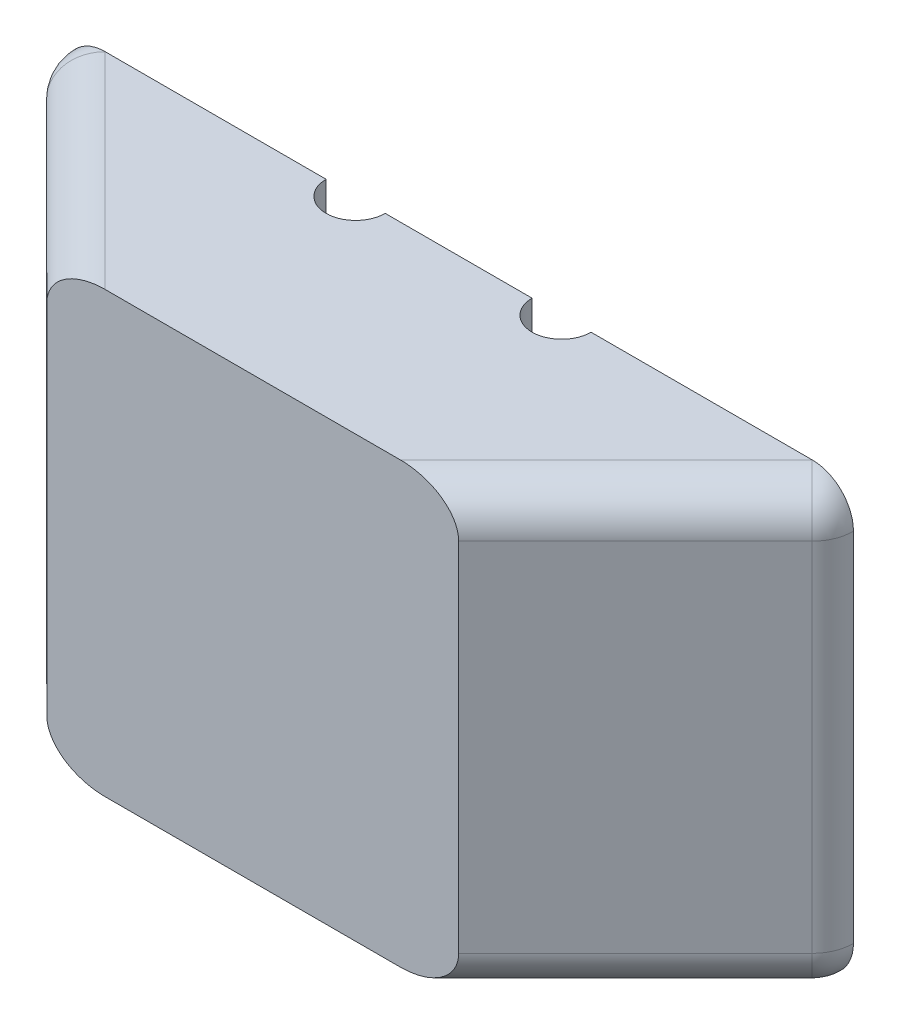
SolidWorks part; units mm, degrees
material "PLA+"
ref_plane "Front Plane" through (0, 0, 0) normal (0, 0, 1) x (1, 0, 0)
ref_plane "Top Plane" through (0, 0, 0) normal (0, 1, 0) x (1, 0, 0)
ref_plane "Right Plane" through (0, 0, 0) normal (1, 0, 0) x (0, 0, -1)
sketch "Sketch1" plane through (0, 0, 0) normal (0, 1, 0) x (1, 0, 0)
  line L0 (15, 15) -> (30, -0.0187)
  line L5 (15, 15) -> (-15, 15)
  line L6 (15, 15) -> (15, -15)
  line L7 (15, -15) -> (-15, -15)
  line L8 (-15, 15) -> (-15, -15)
  line L9 (15, 15) -> (-15, -15) construction
  line L10 (15, -15) -> (-15, 15) construction
  line L11 (30, -0.0187) -> (15, -15)
  line L12 (0, 15) -> (0, -15) construction
  line L13 (-30, -0.0187) -> (-15, -15)
  line L14 (-15, 15) -> (-30, -0.0187)
  point P0 (0, 0)
  dimension "D3" = 15
  dimension "D4" = 90
  dimension "D1" = 30
  dimension "D2" = 21.2
extrude "Boss-Extrude2" add sketch "Sketch1" along normal blind 32 contours L8 L14 L13 | L5 L8 L7 L6 | L11 L0 L6
fillet "Fillet1" radius 3 10 edges at (-22.5, 0, -7.4907) (-22.5, 32, -7.4907) (-22.5, 0, 7.5094) (-22.5, 32, 7.5094) (-30, 16, 0.0187) (30, 16, 0.0187) (22.5, 0, 7.5094) (22.5, 32, 7.5094) (22.5, 0, -7.4907) (22.5, 32, -7.4907)
sketch "Sketch3" plane through (0, 32, 0) normal (0, 1, 0) x (1, 0, 0)
  line L0 (25.7574, 0.016) -> (-25.7574, -0.016) construction
  circle A0 centre (-7.5, -0.0047) radius 2.15
  circle A1 centre (7.5, 0.0047) radius 2.15
  point P5 (0, 0)
  dimension "D2" = 4.3
  dimension "D4" = 4.3
  dimension "D1" = 7.5
  dimension "D3" = 7.5
extrude "Cut-Extrude1" cut sketch "Sketch3" against normal blind 63
sketch "Sketch5" plane through (0, 0, 0) normal (0, 0, 1) x (1, 0, 0)
  line L1 (-35.9882, 37.6239) -> (42.0689, 37.6239)
  line L2 (-35.9882, 37.6239) -> (-35.9882, -0.8462)
  line L3 (-35.9882, -0.8462) -> (42.0689, -0.8462)
  line L4 (42.0689, 37.6239) -> (42.0689, -0.8462)
extrude "Cut-Extrude2" cut sketch "Sketch5" against normal blind 63
